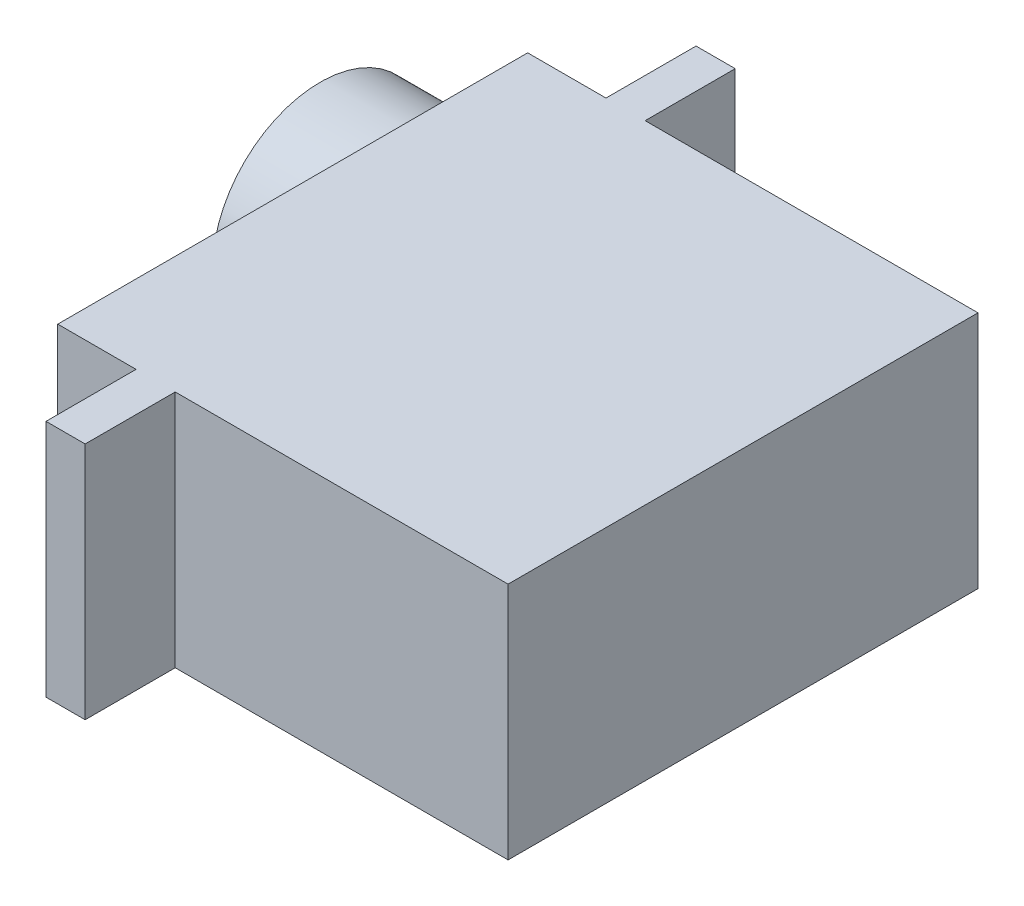
SolidWorks part; units mm, degrees
ref_plane "Front Plane" through (0, 0, 0) normal (0, 0, 1) x (1, 0, 0)
ref_plane "Top Plane" through (0, 0, 0) normal (0, 1, 0) x (1, 0, 0)
ref_plane "Right Plane" through (0, 0, 0) normal (1, 0, 0) x (0, 0, -1)
sketch "草图1" plane through (0, 0, 0) normal (0, 0, 1) x (1, 0, 0)
  line L1 (0, 0) -> (23, 0)
  line L2 (0, 0) -> (0, 12.2)
  line L3 (0, 12.2) -> (23, 12.2)
  line L4 (23, 0) -> (23, 12.2)
  dimension "D1" = 12.2
  dimension "D2" = 23
extrude "凸台-拉伸1" add sketch "草图1" along normal blind 24
sketch "草图2" plane through (0, 0, 24) normal (0, 0, 1) x (1, 0, 0)
  line L0 (23, 12.2) -> (0, 12.2) construction
  line L1 (4, 12.2) -> (6, 12.2)
  line L2 (4, 12.2) -> (4, 0)
  line L3 (4, 0) -> (6, 0)
  line L4 (6, 12.2) -> (6, 0)
  line L5 (0, 0) -> (23, 0) construction
  line L6 (0, 12.2) -> (0, 0) construction
  dimension "D1" = 4
  dimension "D2" = 2
extrude "凸台-拉伸2" add sketch "草图2" along normal blind 4.6 and the other way blind 28.6
sketch "草图3" plane through (0, 0, 0) normal (-1, 0, 0) x (0, 0, 1)
  line L0 (0, 12.2) -> (0, 0) construction
  line L1 (24, 12.2) -> (0, 12.2) construction
  circle A0 centre (6, 6.1) radius 5.5
  dimension "D2" = 6.1
  dimension "D3" = 11
  dimension "D1" = 6
extrude "凸台-拉伸3" add sketch "草图3" along normal blind 4.6
